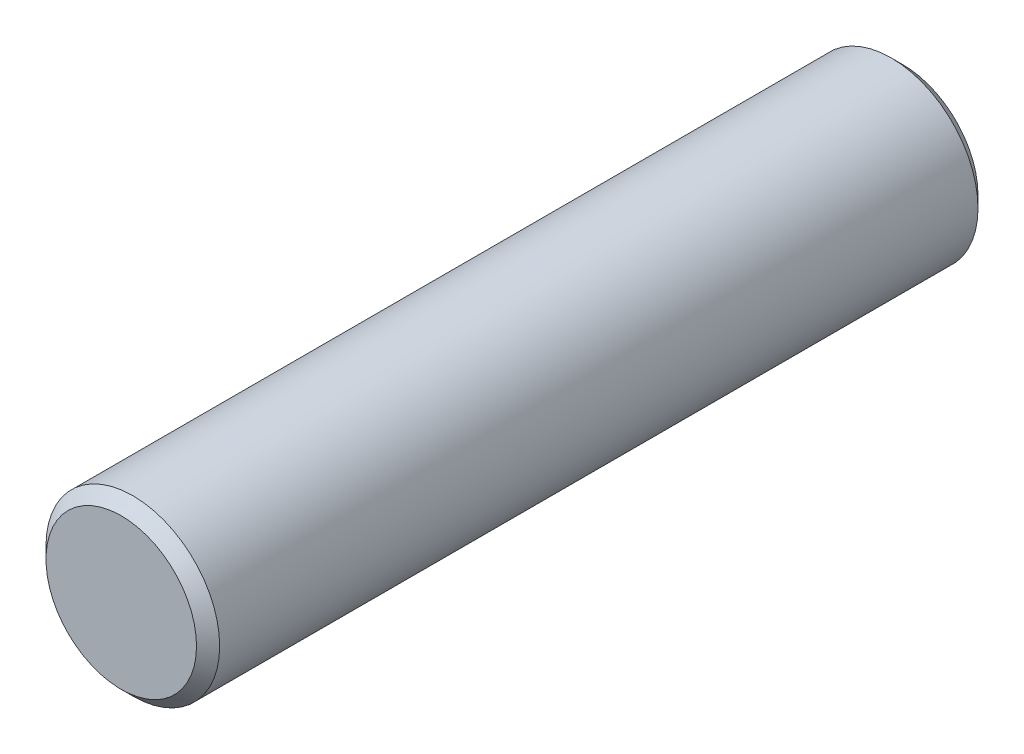
SolidWorks part; units mm, degrees
ref_plane "Front Plane" through (0, 0, 0) normal (0, 0, 1) x (1, 0, 0)
ref_plane "Top Plane" through (0, 0, 0) normal (0, 1, 0) x (1, 0, 0)
ref_plane "Right Plane" through (0, 0, 0) normal (1, 0, 0) x (0, 0, -1)
sketch "Sketch1" plane through (0, 0, 0) normal (0, 0, 1) x (1, 0, 0)
  circle A0 centre (0, 0) radius 1.5
  dimension "D1" = 3
extrude "Boss-Extrude1" add sketch "Sketch1" against normal mid plane 13.5
chamfer "Chamfer1" distance 0.2 angle 45 1 edges at (1.5, 0, 6.75)
chamfer "Chamfer2" distance 0.2 angle 45 1 edges at (1.5, 0, -6.75)
